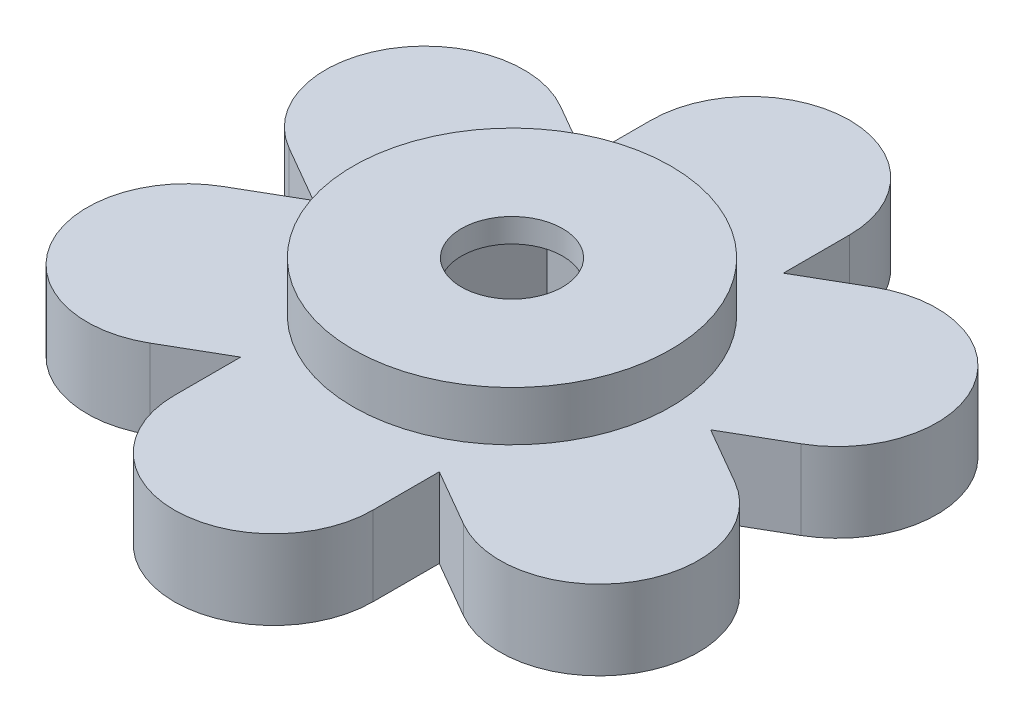
SolidWorks part; units mm, degrees
ref_plane "Front Plane" through (0, 0, 0) normal (0, 0, 1) x (1, 0, 0)
ref_plane "Top Plane" through (0, 0, 0) normal (0, 1, 0) x (1, 0, 0)
ref_plane "Right Plane" through (0, 0, 0) normal (1, 0, 0) x (0, 0, -1)
sketch "Sketch1" plane through (0, 0, 0) normal (0, 1, 0) x (1, 0, 0)
  circle A0 centre (0, 0) radius 8
  dimension "D1" = 16
extrude "Boss-Extrude1" add sketch "Sketch1" along normal blind 6.5
sketch "Sketch4" plane through (0, 0, 0) normal (0, 1, 0) x (1, 0, 0)
  line L0 (-44.2539, 0) -> (44.2539, 0) construction
  line L1 (4.792, 0) -> (2.396, 4.15)
  line L2 (2.396, 4.15) -> (-2.396, 4.15)
  line L3 (-2.396, 4.15) -> (-4.792, 0)
  line L4 (-4.792, 0) -> (-2.396, -4.15)
  line L5 (-2.396, -4.15) -> (2.396, -4.15)
  line L6 (2.396, -4.15) -> (4.792, 0)
  circle A0 centre (0, 0) radius 4.15 construction
  dimension "D1" = 8.3
extrude "Cut-Extrude1" cut sketch "Sketch4" along normal blind 4.1 from offset 1.2
sketch "Sketch5" plane through (0, 0, 0) normal (0, 1, 0) x (1, 0, 0)
  circle A0 centre (0, 0) radius 2.55
  dimension "D1" = 5.1
extrude "Cut-Extrude2" cut sketch "Sketch5" along normal up to surface (6.5 mm away) up to face at (0, 6.5, 8)
sketch "Sketch6" plane through (0, 0, 0) normal (0, 1, 0) x (1, 0, 0)
  line L0 (0, 0) -> (0, 12) construction
  line L1 (0, -44.7868) -> (0, 44.7868) construction
  line L2 (-5, 0) -> (-5, 12)
  line L3 (5, 0) -> (5, 12)
  arc A0 (-5, 0) -> (5, 0) centre (0, 0) ccw
  arc A1 (5, 12) -> (-5, 12) centre (0, 12) ccw
  arc A2 (-5, 6.245) -> (5, 6.245) centre (0, 0) cw
  circle A3 centre (0, 0) radius 8 construction
  point P5 (0, 6)
  dimension "D2" = 5
  dimension "D1" = 12
extrude "Boss-Extrude4" add sketch "Sketch6" along normal blind 4
pattern_circular "CirPattern1" count 6 every 60 about axis through (0, 0, 0) along (0, 1, 0) of "Boss-Extrude4"
equation "\"LeverWidth\"=15"
equation "\"levelLen\"=25"
equation "\"Len\"=12"
equation "\"D1@Sketch6\"=\"Len\""
equation "\"NumArms\"= 6"
equation "\"D1@CirPattern1\"=\"NumArms\""
equation "\"D2@CirPattern1\"=(360/ \"NumArms\")"
equation "\"ArmRad\"= 5"
equation "\"D2@Sketch6\"=\"ArmRad\""
